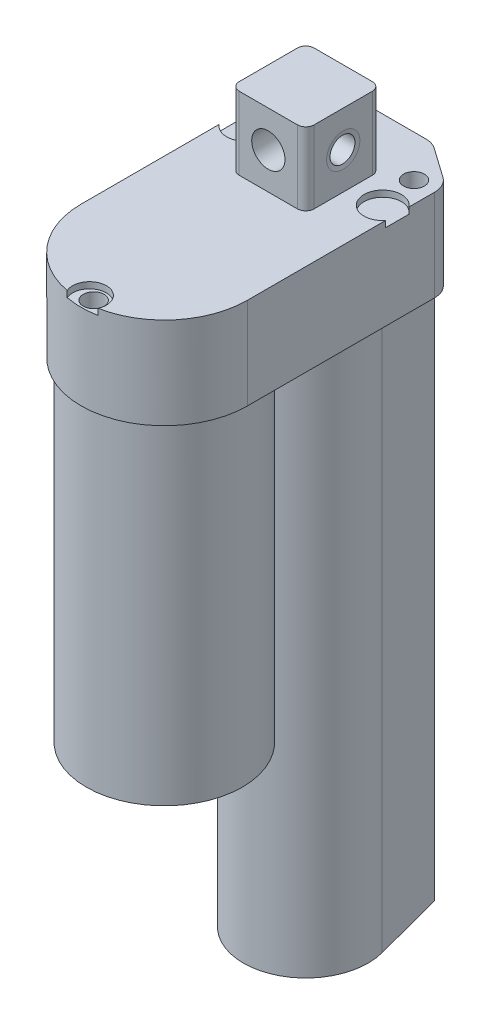
SolidWorks part; units mm, degrees
ref_plane "Alzado" through (0, 0, 0) normal (0, 0, 1) x (1, 0, 0)
ref_plane "Planta" through (0, 0, 0) normal (0, 1, 0) x (1, 0, 0)
ref_plane "Vista lateral" through (0, 0, 0) normal (1, 0, 0) x (0, 0, -1)
sketch "Croquis2" plane through (0, 0, 0) normal (0, 1, 0) x (1, 0, 0)
  line L0 (-17.8783, 49.0885) -> (-10.7759, 54.0885)
  line L1 (0, 0) -> (0, -20) construction
  line L2 (-20, 0) -> (-20, 45)
  line L3 (-7.8977, 55) -> (7.8977, 55)
  line L4 (20, 0) -> (20, 45)
  line L19 (10.7759, 54.0885) -> (17.8783, 49.0885)
  arc A0 (-20, 0) -> (20, 0) centre (0, 0) ccw
  arc A1 (-20, 45) -> (-17.8783, 49.0885) centre (-15, 45) cw
  arc A2 (17.8783, 49.0885) -> (20, 45) centre (15, 45) cw
  arc A3 (10.7759, 54.0885) -> (7.8977, 55) centre (7.8977, 50) ccw
  arc A4 (-7.8977, 55) -> (-10.7759, 54.0885) centre (-7.8977, 50) ccw
  dimension "D1" = 5
  dimension "D2" = 20
  dimension "D3" = 5
  dimension "D4" = 5
  dimension "D5" = 75
  dimension "D6" = 45
  dimension "D7" = 12.1023
  dimension "D8" = 12.1023
extrude "Saliente-Extruir1" add sketch "Croquis2" along normal blind 22
sketch "Croquis3" plane through (0, 22, 0) normal (0, 1, 0) x (1, 0, 0)
  circle A0 centre (-15, 45) radius 2.5
  circle A1 centre (15, 45) radius 2.5
  circle A2 centre (-16.5, 36) radius 4.5
  circle A3 centre (16.5, 36) radius 4.5
extrude "Cortar-Extruir2" cut sketch "Croquis3" against normal blind 1.5
sketch "Croquis4" plane through (0, 22, 0) normal (0, 1, 0) x (1, 0, 0)
  circle A0 centre (-15, 45) radius 2.5
  circle A1 centre (15, 45) radius 2.5
extrude "Cortar-Extruir3" cut sketch "Croquis4" against normal blind 18
sketch "Croquis5" plane through (0, 22, 0) normal (0, 1, 0) x (1, 0, 0)
  line L0 (0, -20) -> (0, -17)
  arc A0 (-20, 0) -> (20, 0) centre (0, 0) ccw construction
  circle A1 centre (0, -17) radius 2.5
  circle A3 centre (0.022, -18) radius 4.0586
extrude "Cortar-Extruir4" cut sketch "Croquis5" against normal blind 1.5 contours A3
sketch "Croquis6" plane through (0, 20.5, 0) normal (0, 1, 0) x (1, 0, 0)
  circle A1 centre (0.0245, -17) radius 2.5
extrude "Cortar-Extruir5" cut sketch "Croquis6" against normal blind 15
sketch "Croquis7" plane through (0, 20.5, 0) normal (0, 1, 0) x (1, 0, 0)
  line L0 (0.0245, -20) -> (0.0245, -16.2667) construction
  line L1 (7.8977, 55) -> (-7.8977, 55) construction
  line L2 (7, 25) -> (-7, 25)
  line L3 (9, 27) -> (9, 41)
  line L4 (7, 43) -> (-7, 43)
  line L5 (-9, 27) -> (-9, 41)
  line L6 (9, 25) -> (-9, 43) construction
  line L7 (0, 55) -> (0, 34) construction
  line L11 (9, 43) -> (-9, 25) construction
  arc A0 (-3.6825, -19.6581) -> (3.7305, -19.649) centre (0, 0) ccw construction
  arc A1 (-9, 27) -> (-7, 25) centre (-7, 27) ccw
  arc A2 (9, 27) -> (7, 25) centre (7, 27) cw
  arc A3 (7, 43) -> (9, 41) centre (7, 41) cw
  arc A4 (-7, 43) -> (-9, 41) centre (-7, 41) ccw
  point P5 (0, 34)
  point P28 (0, 34)
  dimension "D1" = 2
  dimension "D4" = 2
  dimension "D2" = 18
  dimension "D3" = 30
  dimension "D5" = 18
extrude "Saliente-Extruir2" add sketch "Croquis7" along normal blind 19
sketch "Croquis8" plane through (-9, 0, 0) normal (-1, 0, 0) x (0, 0, 1)
  line L0 (-34, 39.5) -> (-34, 22) construction
  line L1 (-41, 39.5) -> (-27, 39.5) construction
  line L2 (-27, 22) -> (-41, 22) construction
  line L3 (-41, 30.75) -> (-27, 30.75) construction
  line L4 (-41, 39.5) -> (-41, 22) construction
  line L5 (-27, 39.5) -> (-27, 22) construction
  circle A1 centre (-34, 30.75) radius 3
extrude "Cortar-Extruir7" cut sketch "Croquis8" against normal blind 19
sketch "Croquis9" plane through (-9, 0, 0) normal (-1, 0, 0) x (0, 0, 1)
  circle A0 centre (-34, 30.75) radius 4
extrude "Cortar-Extruir10" cut sketch "Croquis9" against normal blind 0.5 draft 80
sketch "Croquis10" plane through (9, 0, 0) normal (1, 0, 0) x (0, 0, -1)
  circle A0 centre (34, 30.75) radius 4
extrude "Cortar-Extruir11" cut sketch "Croquis10" against normal blind 0.5 draft 80
sketch "Croquis11" plane through (0, 0, 0) normal (0, -1, 0) x (1, 0, 0)
  line L0 (0, 0) -> (0, -68) construction
  line L1 (-20, -45) -> (-20, 0) construction
  line L2 (0, -25) -> (0, -43) construction
  line L4 (-10, -55) -> (-14.5094, -37.8051)
  line L5 (-10, -55) -> (10, -55)
  line L6 (10, -55) -> (14.5094, -37.8051)
  line L7 (7, -25) -> (-7, -25) construction
  line L8 (7.8977, -55) -> (-7.8977, -55) construction
  line L9 (-7, -43) -> (7, -43) construction
  line L10 (-9, -34) -> (8.8237, -34) construction
  line L11 (-9, -27) -> (-9, -41) construction
  line L12 (8.8237, -37) -> (8.8237, -31) construction
  arc A1 (14.5094, -37.8051) -> (-14.5094, -37.8051) centre (0, -34) ccw
  dimension "D1" = 20
  dimension "D2" = 0
  dimension "D6" = 15
  dimension "D4" = 20
  dimension "D5" = 10
extrude "Saliente-Extruir3" add sketch "Croquis11" along normal blind 135.5
sketch "Croquis12" plane through (0, -135.5, 0) normal (0, -1, 0) x (1, 0, 0)
  line L0 (0, -25) -> (0, -43) construction
  line L1 (7, -25) -> (-7, -25) construction
  line L2 (-7, -43) -> (7, -43) construction
  line L3 (0, -34) -> (10.6556, -34) construction
  circle A0 centre (0, -34) radius 10
  dimension "D1" = 20
extrude "Cortar-Extruir12" cut sketch "Croquis12" against normal blind 100
sketch "Croquis15" plane through (0, 0, 0) normal (0, -1, 0) x (1, 0, 0)
  line L0 (0, 0) -> (0, 27.3935) construction
  line L1 (0, 0) -> (-32.2533, 0) construction
  circle A0 centre (0, 0) radius 18.75
  dimension "D1" = 37.5
extrude "Saliente-Extruir10" add sketch "Croquis15" along normal blind 80
sketch "Croquis16" plane through (0, 0, -43) normal (0, 0, -1) x (-1, 0, 0)
  line L0 (0, 39.5) -> (0, 22) construction
  line L1 (-7, 39.5) -> (7, 39.5) construction
  line L2 (-7.8977, 22) -> (7.8977, 22) construction
  circle A0 centre (0, 30.75) radius 4
  dimension "D1" = 8
extrude "Cortar-Extruir13" cut sketch "Croquis16" against normal through all
